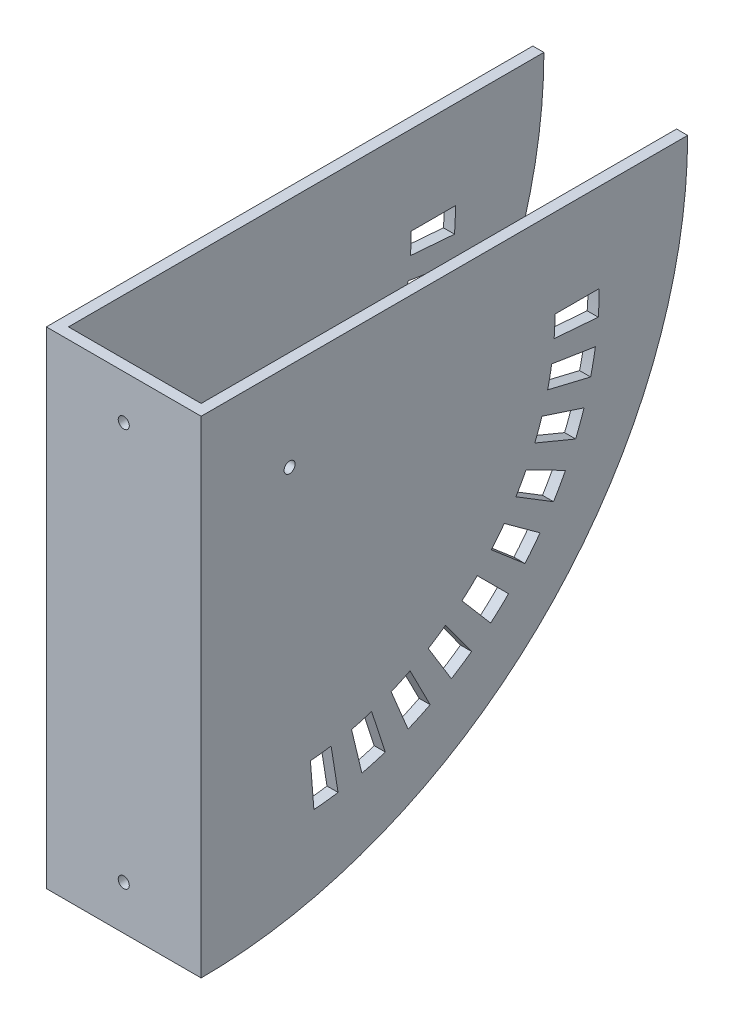
SolidWorks part; units mm, degrees
material "Plain Carbon Steel"
ref_plane "Front Plane" through (0, 0, 0) normal (0, 0, 1) x (1, 0, 0)
ref_plane "Top Plane" through (0, 0, 0) normal (0, 1, 0) x (1, 0, 0)
ref_plane "Right Plane" through (0, 0, 0) normal (1, 0, 0) x (0, 0, -1)
sketch "Sketch1" plane through (0, 0, 0) normal (0, 0, 1) x (1, 0, 0)
  line L0 (-35, -110) -> (-35, 110)
  line L1 (-30, -110) -> (30, -110)
  line L2 (-30, -110) -> (-30, 110)
  line L3 (-30, 110) -> (30, 110)
  line L4 (30, -110) -> (30, 110)
  line L5 (-30, -110) -> (30, 110) construction
  line L6 (-30, 110) -> (30, -110) construction
  line L8 (35, -110) -> (35, 110)
  line L10 (-30, 110) -> (-35, 110)
  line L11 (-35, 110) -> (35, 110)
  line L12 (-35, 115) -> (35, 115) construction
  line L13 (-35, -115) -> (-35, 115) construction
  line L14 (35, -115) -> (35, 115) construction
  line L15 (0, -110) -> (-35, -110)
  line L16 (-35, -110) -> (35, -110)
  line L18 (-35, -115) -> (35, -115) construction
  point P0 (0, 0)
  dimension "D1" = 60
  dimension "D3" = 220
  dimension "D2" = 5
extrude "Boss-Extrude1" add sketch "Sketch1" along normal blind 220 contours L4 L16 L8 L11 | L15 L2 L10 L0
sketch "Sketch2" plane through (0, 0, 220) normal (0, 0, 1) x (1, 0, 0)
  line L1 (-30, 110) -> (30, 110)
  line L2 (-30, 110) -> (-30, -110)
  line L3 (-30, -110) -> (30, -110)
  line L4 (30, 110) -> (30, -110)
extrude "Boss-Extrude2" add sketch "Sketch2" against normal blind 5
sketch "Sketch3" plane through (-35, 0, 0) normal (-1, 0, 0) x (0, 0, 1)
  line L0 (0, 110) -> (0, -110)
  line L1 (0, -110) -> (220, -110)
  arc A0 (0, 110) -> (220, -110) centre (220, 110) ccw
extrude "Cut-Extrude1" cut sketch "Sketch3" against normal blind 110
sketch "Sketch7" plane through (0, 0, 215) normal (0, 0, -1) x (-1, 0, 0)
  line L0 (-30, 110) -> (30, 110) construction
  circle A0 centre (0, 90) radius 2.5
  circle A1 centre (0, -90) radius 2.5
  dimension "D2" = 5
  dimension "D4" = 5
  dimension "D1" = 20
  dimension "D3" = 180
extrude "Cut-Extrude6" cut sketch "Sketch7" against normal blind 134
sketch "Sketch9" plane through (-35, 0, 0) normal (-1, 0, 0) x (0, 0, 1)
  line L0 (220, -110) -> (220, 110) construction
  line L1 (220, 110) -> (0, 110) construction
  line L23 (60, 70) -> (40, 70)
  line L24 (60.3699, 60.5849) -> (40.4316, 59.0157)
  line L25 (61.4774, 51.2279) -> (41.7236, 48.0992)
  line L26 (63.3156, 41.9866) -> (43.8682, 37.3176)
  line L27 (65.8732, 32.918) -> (46.8521, 26.7376)
  line L28 (69.1345, 24.078) -> (50.6569, 16.4243)
  line L29 (73.0792, 15.5211) -> (55.2591, 6.4413)
  line L30 (77.6832, 7.3002) -> (60.6304, -3.1498)
  line L31 (82.918, -0.5342) -> (66.7376, -12.2899)
  line L32 (88.7513, -7.9338) -> (73.5432, -20.9227)
  line L33 (95.1472, -14.8528) -> (81.0051, -28.9949)
  line L34 (102.0662, -21.2487) -> (89.0773, -36.4568)
  line L35 (109.4658, -27.082) -> (97.7101, -43.2624)
  line L36 (117.3002, -32.3168) -> (106.8502, -49.3696)
  line L37 (125.5211, -36.9208) -> (116.4413, -54.7409)
  line L38 (134.078, -40.8655) -> (126.4243, -59.3431)
  line L39 (142.918, -44.1268) -> (136.7376, -63.1479)
  line L40 (151.9866, -46.6844) -> (147.3176, -66.1318)
  line L41 (161.2279, -48.5226) -> (158.0992, -68.2764)
  line L42 (170.5849, -49.6301) -> (169.0157, -69.5684)
  line L43 (180, -50) -> (180, -70)
  circle A0 centre (180, 70) radius 2.5
  arc A1 (40, 70) -> (180, -70) centre (180, 70) ccw
  arc A2 (60, 70) -> (180, -50) centre (180, 70) ccw
  point P32 (180, 70)
  dimension "D1" = 5
  dimension "D5" = 280
  dimension "D6" = 240
  dimension "D2" = 40
  dimension "D3" = 40
extrude "Cut-Extrude8" cut sketch "Sketch9" against normal blind 134 contours A2 L23 A1 L24 | A2 L25 A1 L26 | A2 L27 A1 L28 | A2 L29 A1 L30 | A2 L31 A1 L32 | A2 L33 A1 L34 | A2 L35 A1 L36 | A2 L37 A1 L38 | A2 L39 A1 L40 | A2 L41 A1 L42 | A0
